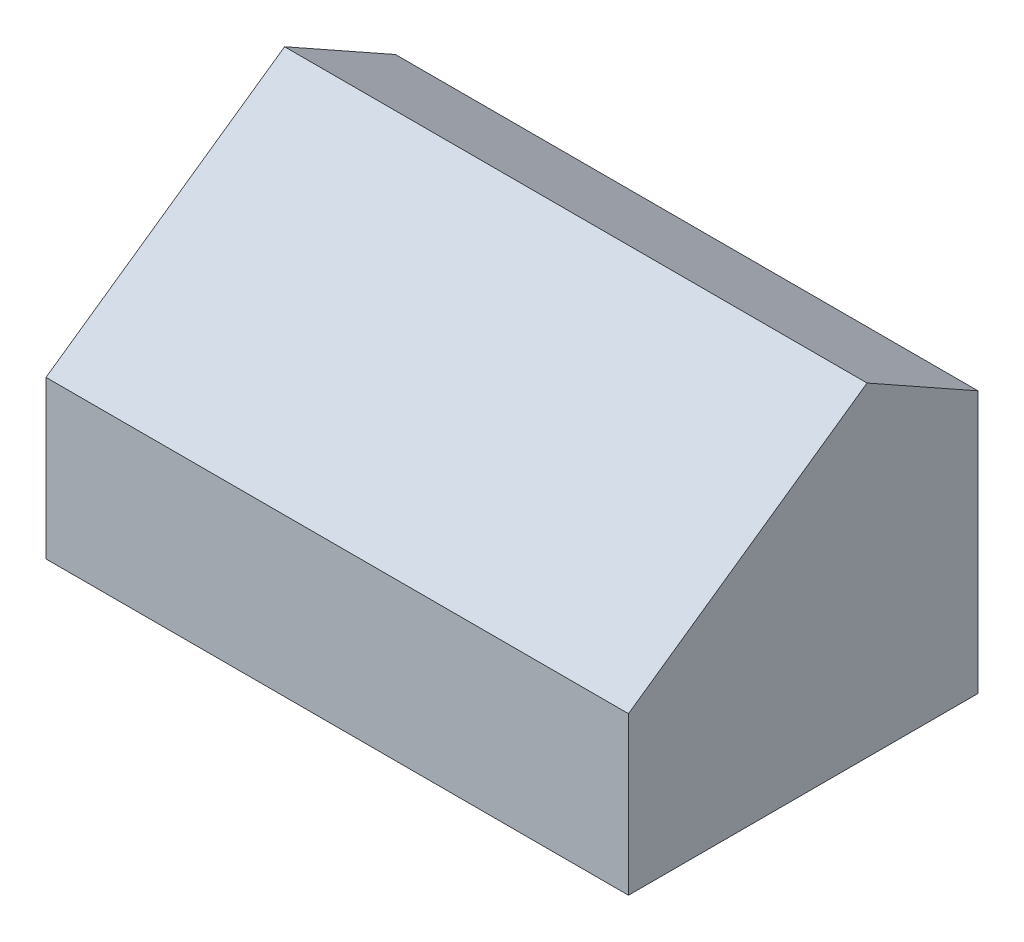
SolidWorks part; units mm, degrees
ref_plane "Front Plane" through (0, 0, 0) normal (0, 0, 1) x (1, 0, 0)
ref_plane "Top Plane" through (0, 0, 0) normal (0, 1, 0) x (1, 0, 0)
ref_plane "Right Plane" through (0, 0, 0) normal (1, 0, 0) x (0, 0, -1)
sketch "Sketch1" plane through (0, 0, 0) normal (1, 0, 0) x (0, 0, -1)
  line L0 (0, 0) -> (0, 27)
  line L1 (0, 27) -> (40.9576, 55.6788)
  line L2 (40.9576, 55.6788) -> (60, 45)
  line L3 (60, 45) -> (60, 0)
  line L4 (60, 0) -> (0, 0)
  point P6 (60, 47.0039)
  point P7 (41.4665, 56.0352)
  dimension "D1" = 60
  dimension "D2" = 35
  dimension "D3" = 27
  dimension "D4" = 45
  dimension "D5" = 50
extrude "Boss-Extrude1" add sketch "Sketch1" along normal blind 100
sketch "Sketch2" plane through (0, 0, 0) normal (0, -1, 0) x (1, 0, 0)
  line L0 (100, -60) -> (83.923, -60) construction
  line L1 (100, 0) -> (100, -60) construction
  line L2 (100, 0) -> (83.923, -60) construction
  line L4 (100, -60) -> (0, -60) construction
  point P0 (83.923, -60)
  point P5 (88.8877, -60)
  dimension "D2" = 15
ref_plane "Plane2" through (90.0376, -17.7468, -24.1255) normal (0.9489, -0.187, -0.2543) x (-0.2537, 0.0272, -0.9669)
